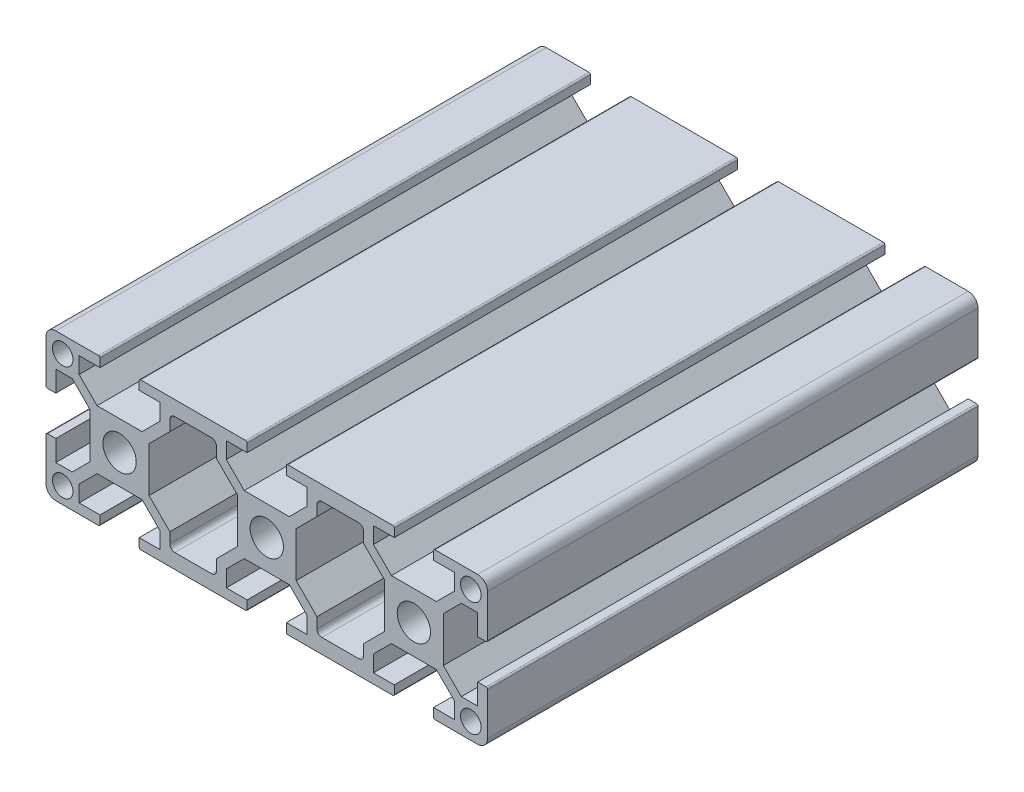
SolidWorks part; units mm, degrees
ref_plane "前视基准面" through (0, 0, 0) normal (0, 0, 1) x (1, 0, 0)
ref_plane "上视基准面" through (0, 0, 0) normal (0, 1, 0) x (1, 0, 0)
ref_plane "右视基准面" through (0, 0, 0) normal (1, 0, 0) x (0, 0, -1)
sketch "草图1" plane through (0, 0, 0) normal (0, 0, 1) x (1, 0, 0)
  line B0 (-15, 13) -> (-15, 4.3)
  line B1 (-14.7, 4) -> (-13, 4)
  line B2 (-13, 4) -> (-13, 8.25)
  line B3 (-13, 8.25) -> (-9.6642, 8.25)
  line B4 (-9.6642, 8.25) -> (-6, 4.5858)
  line B5 (-6, 4.5858) -> (-6, -4.5858)
  line B6 (-6, -4.5858) -> (-9.6642, -8.25)
  line B7 (-9.6642, -8.25) -> (-13, -8.25)
  line B8 (-13, -8.25) -> (-13, -4)
  line B9 (-13, -4) -> (-14.7, -4)
  line B10 (-15, -4.3) -> (-15, -13)
  line B11 (-13, -15) -> (-4.3, -15)
  line B12 (-4, -14.7) -> (-4, -13)
  line B13 (-4, -13) -> (-8.25, -13)
  line B14 (-8.25, -13) -> (-8.25, -9.6642)
  line B15 (-8.25, -9.6642) -> (-4.5858, -6)
  line B16 (-4.5858, -6) -> (4.5858, -6)
  line B17 (4.5858, -6) -> (8.25, -9.6642)
  line B18 (8.25, -9.6642) -> (8.25, -13)
  line B19 (8.25, -13) -> (4, -13)
  line B20 (4, -13) -> (4, -14.7)
  line B21 (4.3, -15) -> (25.7, -15)
  line B22 (26, -14.7) -> (26, -13)
  line B23 (26, -13) -> (21.75, -13)
  line B24 (21.75, -13) -> (21.75, -9.6642)
  line B25 (21.75, -9.6642) -> (25.4142, -6)
  line B26 (25.4142, -6) -> (34.5858, -6)
  line B27 (34.5858, -6) -> (38.25, -9.6642)
  line B28 (38.25, -9.6642) -> (38.25, -13)
  line B29 (38.25, -13) -> (34, -13)
  line B30 (34, -13) -> (34, -14.7)
  line B31 (34.3, -15) -> (55.7, -15)
  line B32 (56, -14.7) -> (56, -13)
  line B33 (56, -13) -> (51.75, -13)
  line B34 (51.75, -13) -> (51.75, -9.6642)
  line B35 (51.75, -9.6642) -> (55.4142, -6)
  line B36 (55.4142, -6) -> (64.5858, -6)
  line B37 (64.5858, -6) -> (68.25, -9.6642)
  line B38 (68.25, -9.6642) -> (68.25, -13)
  line B39 (68.25, -13) -> (64, -13)
  line B40 (64, -13) -> (64, -14.7)
  line B41 (64.3, -15) -> (73, -15)
  line B42 (75, -13) -> (75, -4.3)
  line B43 (74.7, -4) -> (73, -4)
  line B44 (73, -4) -> (73, -8.25)
  line B45 (73, -8.25) -> (69.6642, -8.25)
  line B46 (69.6642, -8.25) -> (66, -4.5858)
  line B47 (66, -4.5858) -> (66, 4.5858)
  line B48 (66, 4.5858) -> (69.6642, 8.25)
  line B49 (69.6642, 8.25) -> (73, 8.25)
  line B50 (73, 8.25) -> (73, 4)
  line B51 (73, 4) -> (74.7, 4)
  line B52 (75, 4.3) -> (75, 13)
  line B53 (73, 15) -> (64.3, 15)
  line B54 (64, 14.7) -> (64, 13)
  line B55 (64, 13) -> (68.25, 13)
  line B56 (68.25, 13) -> (68.25, 9.6642)
  line B57 (68.25, 9.6642) -> (64.5858, 6)
  line B58 (64.5858, 6) -> (55.4142, 6)
  line B59 (55.4142, 6) -> (51.75, 9.6642)
  line B60 (51.75, 9.6642) -> (51.75, 13)
  line B61 (51.75, 13) -> (56, 13)
  line B62 (56, 13) -> (56, 14.7)
  line B63 (55.7, 15) -> (34.3, 15)
  line B64 (34, 14.7) -> (34, 13)
  line B65 (34, 13) -> (38.25, 13)
  line B66 (38.25, 13) -> (38.25, 9.6642)
  line B67 (38.25, 9.6642) -> (34.5858, 6)
  line B68 (34.5858, 6) -> (25.4142, 6)
  line B69 (25.4142, 6) -> (21.75, 9.6642)
  line B70 (21.75, 9.6642) -> (21.75, 13)
  line B71 (21.75, 13) -> (26, 13)
  line B72 (26, 13) -> (26, 14.7)
  line B73 (25.7, 15) -> (4.3, 15)
  line B74 (4, 14.7) -> (4, 13)
  line B75 (4, 13) -> (8.25, 13)
  line B76 (8.25, 13) -> (8.25, 9.6642)
  line B77 (8.25, 9.6642) -> (4.5858, 6)
  line B78 (4.5858, 6) -> (-4.5858, 6)
  line B79 (-4.5858, 6) -> (-8.25, 9.6642)
  line B80 (-8.25, 9.6642) -> (-8.25, 13)
  line B81 (-8.25, 13) -> (-4, 13)
  line B82 (-4, 13) -> (-4, 14.7)
  line B83 (-4.3, 15) -> (-13, 15)
  line B84 (40.25, 11) -> (40.25, 10)
  line B85 (40.25, 10) -> (40.25, 8.8358)
  line B86 (40.25, 8.8358) -> (36, 4.5858)
  line B87 (36, 4.5858) -> (36, -4.5858)
  line B88 (36, -4.5858) -> (40.25, -8.8358)
  line B89 (40.25, -8.8358) -> (40.25, -10)
  line B90 (40.25, -10) -> (40.25, -11)
  line B91 (41.25, -12) -> (48.75, -12)
  line B92 (49.75, -11) -> (49.75, -10)
  line B93 (49.75, -10) -> (49.75, -8.8358)
  line B94 (49.75, -8.8358) -> (54, -4.5858)
  line B95 (54, -4.5858) -> (54, 4.5858)
  line B96 (54, 4.5858) -> (49.75, 8.8358)
  line B97 (49.75, 8.8358) -> (49.75, 10)
  line B98 (49.75, 10) -> (49.75, 11)
  line B99 (48.75, 12) -> (41.25, 12)
  line B100 (18.75, 12) -> (11.25, 12)
  line B101 (10.25, 11) -> (10.25, 10)
  line B102 (10.25, 10) -> (10.25, 8.8358)
  line B103 (10.25, 8.8358) -> (6, 4.5858)
  line B104 (6, 4.5858) -> (6, -4.5858)
  line B105 (6, -4.5858) -> (10.25, -8.8358)
  line B106 (10.25, -8.8358) -> (10.25, -10)
  line B107 (10.25, -10) -> (10.25, -11)
  line B108 (11.25, -12) -> (18.75, -12)
  line B109 (19.75, -11) -> (19.75, -10)
  line B110 (19.75, -10) -> (19.75, -8.8358)
  line B111 (19.75, -8.8358) -> (24, -4.5858)
  line B112 (24, -4.5858) -> (24, 4.5858)
  line B113 (24, 4.5858) -> (19.75, 8.8358)
  line B114 (19.75, 8.8358) -> (19.75, 10)
  line B115 (19.75, 10) -> (19.75, 11)
  arc B116 (-13, 15) -> (-15, 13) centre (-13, 13) ccw
  arc B117 (-15, 4.3) -> (-14.7, 4) centre (-14.7, 4.3) ccw
  arc B118 (-14.7, -4) -> (-15, -4.3) centre (-14.7, -4.3) ccw
  arc B119 (-15, -13) -> (-13, -15) centre (-13, -13) ccw
  arc B120 (-4.3, -15) -> (-4, -14.7) centre (-4.3, -14.7) ccw
  arc B121 (4, -14.7) -> (4.3, -15) centre (4.3, -14.7) ccw
  arc B122 (25.7, -15) -> (26, -14.7) centre (25.7, -14.7) ccw
  arc B123 (34, -14.7) -> (34.3, -15) centre (34.3, -14.7) ccw
  arc B124 (55.7, -15) -> (56, -14.7) centre (55.7, -14.7) ccw
  arc B125 (64, -14.7) -> (64.3, -15) centre (64.3, -14.7) ccw
  arc B126 (73, -15) -> (75, -13) centre (73, -13) ccw
  arc B127 (75, -4.3) -> (74.7, -4) centre (74.7, -4.3) ccw
  arc B128 (74.7, 4) -> (75, 4.3) centre (74.7, 4.3) ccw
  arc B129 (75, 13) -> (73, 15) centre (73, 13) ccw
  arc B130 (64.3, 15) -> (64, 14.7) centre (64.3, 14.7) ccw
  arc B131 (56, 14.7) -> (55.7, 15) centre (55.7, 14.7) ccw
  arc B132 (34.3, 15) -> (34, 14.7) centre (34.3, 14.7) ccw
  arc B133 (26, 14.7) -> (25.7, 15) centre (25.7, 14.7) ccw
  arc B134 (4.3, 15) -> (4, 14.7) centre (4.3, 14.7) ccw
  arc B135 (-4, 14.7) -> (-4.3, 15) centre (-4.3, 14.7) ccw
  arc B136 (41.25, 12) -> (40.25, 11) centre (41.25, 11) ccw
  arc B137 (40.25, -11) -> (41.25, -12) centre (41.25, -11) ccw
  arc B138 (48.75, -12) -> (49.75, -11) centre (48.75, -11) ccw
  arc B139 (49.75, 11) -> (48.75, 12) centre (48.75, 11) ccw
  arc B140 (19.75, 11) -> (18.75, 12) centre (18.75, 11) ccw
  arc B141 (11.25, 12) -> (10.25, 11) centre (11.25, 11) ccw
  arc B142 (10.25, -11) -> (11.25, -12) centre (11.25, -11) ccw
  arc B143 (18.75, -12) -> (19.75, -11) centre (18.75, -11) ccw
  circle B144 centre (0, 0) radius 3.4
  circle B145 centre (60, 0) radius 3.4
  circle B146 centre (30, 0) radius 3.4
  circle B147 centre (-11.6, -11.65) radius 2.1
  circle B148 centre (71.6, -11.65) radius 2.1
  circle B149 centre (71.6, 11.65) radius 2.1
  circle B150 centre (-11.6, 11.65) radius 2.1
sketch_block_instance "A$C6C897AF7-1"
sketch_block "A$C6C897AF7"
extrude "凸台-拉伸1" add sketch "草图1" along normal blind 100
